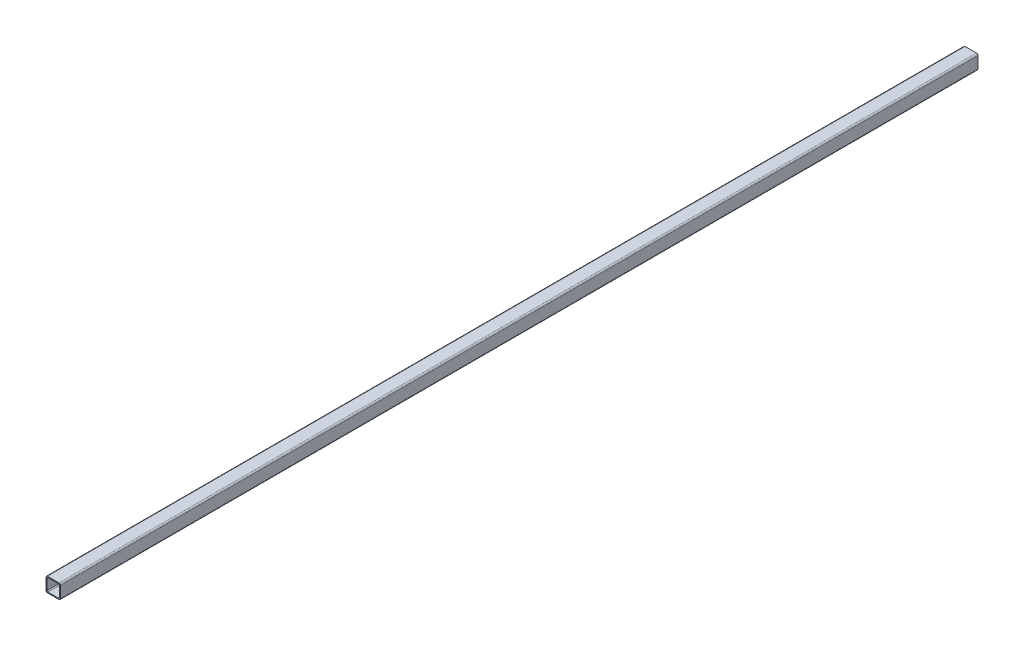
SolidWorks part; units mm, degrees
material "AISI 1020"
ref_plane "Спереди" through (0, 0, 0) normal (0, 0, 1) x (1, 0, 0)
ref_plane "Сверху" through (0, 0, 0) normal (0, 1, 0) x (1, 0, 0)
ref_plane "Справа" through (0, 0, 0) normal (1, 0, 0) x (0, 0, -1)
sketch "Эскиз1" plane through (0, 0, 0) normal (0, 0, 1) x (1, 0, 0)
  line L0 (-482.5, 30) -> (0, 30) construction
  line L1 (0, 27) -> (0, 3) construction
  line B0 (-27, 30) -> (-3, 30)
  line B1 (-30, 27) -> (-30, 3)
  line B2 (-27, 0) -> (-3, 0)
  line B3 (0, 27) -> (0, 3)
  line B4 (-26, 28) -> (-4, 28)
  line B5 (-28, 26) -> (-28, 4)
  line B6 (-26, 2) -> (-4, 2)
  line B7 (-2, 26) -> (-2, 4)
  arc B8 (-30, 3) -> (-27, 0) centre (-27, 3) ccw
  arc B9 (-3, 0) -> (0, 3) centre (-3, 3) ccw
  arc B10 (-3, 30) -> (0, 27) centre (-3, 27) cw
  arc B11 (-27, 30) -> (-30, 27) centre (-27, 27) ccw
  arc B12 (-28, 4) -> (-26, 2) centre (-26, 4) ccw
  arc B13 (-4, 2) -> (-2, 4) centre (-4, 4) ccw
  arc B14 (-4, 28) -> (-2, 26) centre (-4, 26) cw
  arc B15 (-26, 28) -> (-28, 26) centre (-26, 26) ccw
sketch_block_instance "Блок-30х30х2-1"
sketch_block "Блок-30х30х2" parameters "D3"=3, "D4"=2, "D1"=30, "D2"=2
extrude "Бобышка-Вытянуть1" add sketch "Эскиз1" against normal up to surface (1910 mm away)
